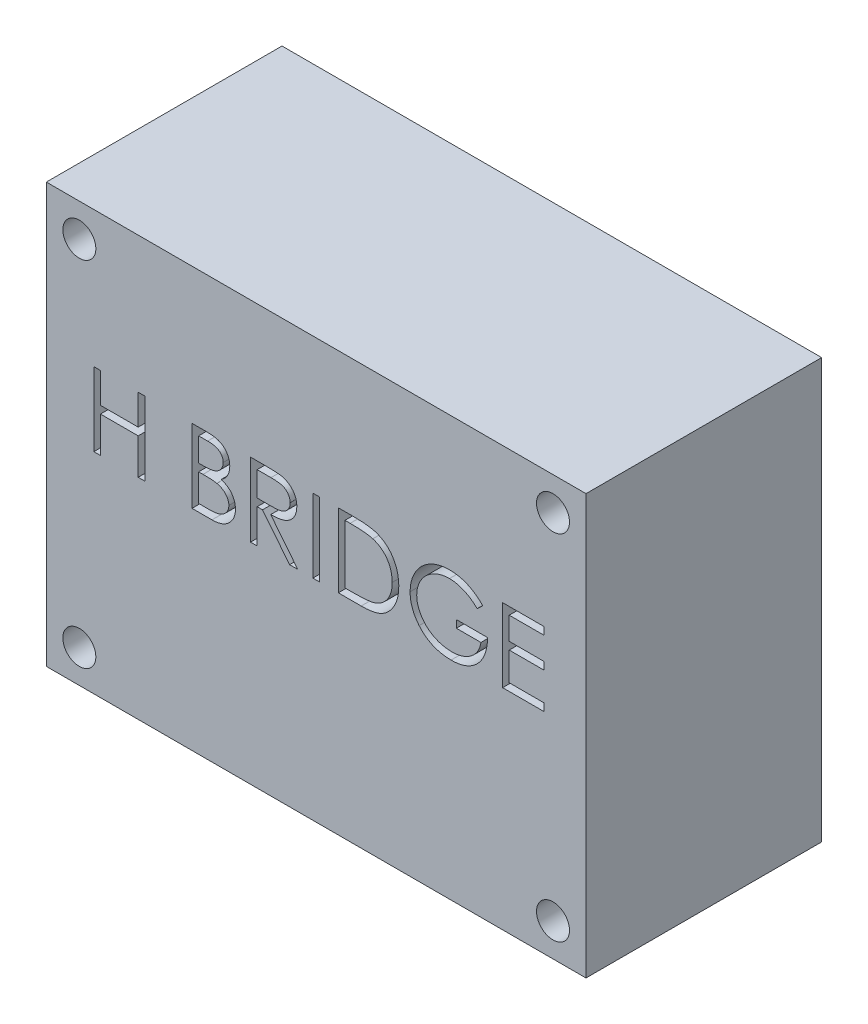
SolidWorks part; units mm, degrees
ref_plane "Front Plane" through (0, 0, 0) normal (0, 0, 1) x (1, 0, 0)
ref_plane "Top Plane" through (0, 0, 0) normal (0, 1, 0) x (1, 0, 0)
ref_plane "Right Plane" through (0, 0, 0) normal (1, 0, 0) x (0, 0, -1)
sketch "Sketch1" plane through (0, 0, 0) normal (0, 0, 1) x (1, 0, 0)
  line L1 (-84.1583, 38.6592) -> (-25.9923, 38.6592)
  line L2 (-84.1583, 38.6592) -> (-84.1583, -6.5528)
  line L3 (-84.1583, -6.5528) -> (-25.9923, -6.5528)
  line L4 (-25.9923, 38.6592) -> (-25.9923, -6.5528)
  dimension "D1" = 58.166
  dimension "D2" = 45.212
extrude "Boss-Extrude1" add sketch "Sketch1" along normal blind 25.4
sketch "Sketch2" plane through (0, 0, 25.4) normal (0, 0, 1) x (1, 0, 0)
  line L0 (-25.9923, 38.6592) -> (-84.1583, 38.6592) construction
  line L1 (-25.9923, -6.5528) -> (-25.9923, 38.6592) construction
  line L2 (-55.0753, 38.6592) -> (-55.0753, -6.5528) construction
  line L3 (-84.1583, -6.5528) -> (-25.9923, -6.5528) construction
  line L4 (-25.9923, 16.0532) -> (-84.1583, 16.0532) construction
  line L5 (-84.1583, 38.6592) -> (-84.1583, -6.5528) construction
  circle A0 centre (-29.5483, 35.1032) radius 1.778
  circle A1 centre (-80.6023, 35.1032) radius 1.778
  circle A2 centre (-29.5483, -2.9968) radius 1.778
  circle A3 centre (-80.6023, -2.9968) radius 1.778
  dimension "D1" = 3.556
  dimension "D2" = 3.556
  dimension "D3" = 3.556
extrude "Cut-Extrude1" cut sketch "Sketch2" against normal through all
sketch "Sketch3" plane through (0, 0, 25.4) normal (0, 0, 1) x (1, 0, 0)
  line L0 (-84.1583, 16.0532) -> (-25.9923, 16.0532) construction
  line L1 (-84.1583, 38.6592) -> (-84.1583, -6.5528) construction
  line L2 (-25.9923, -6.5528) -> (-25.9923, 38.6592) construction
  text T0 "H BRIDGE" font "Century Gothic" height in points 30
extrude "Cut-Extrude2" cut sketch "Sketch3" against normal through all
